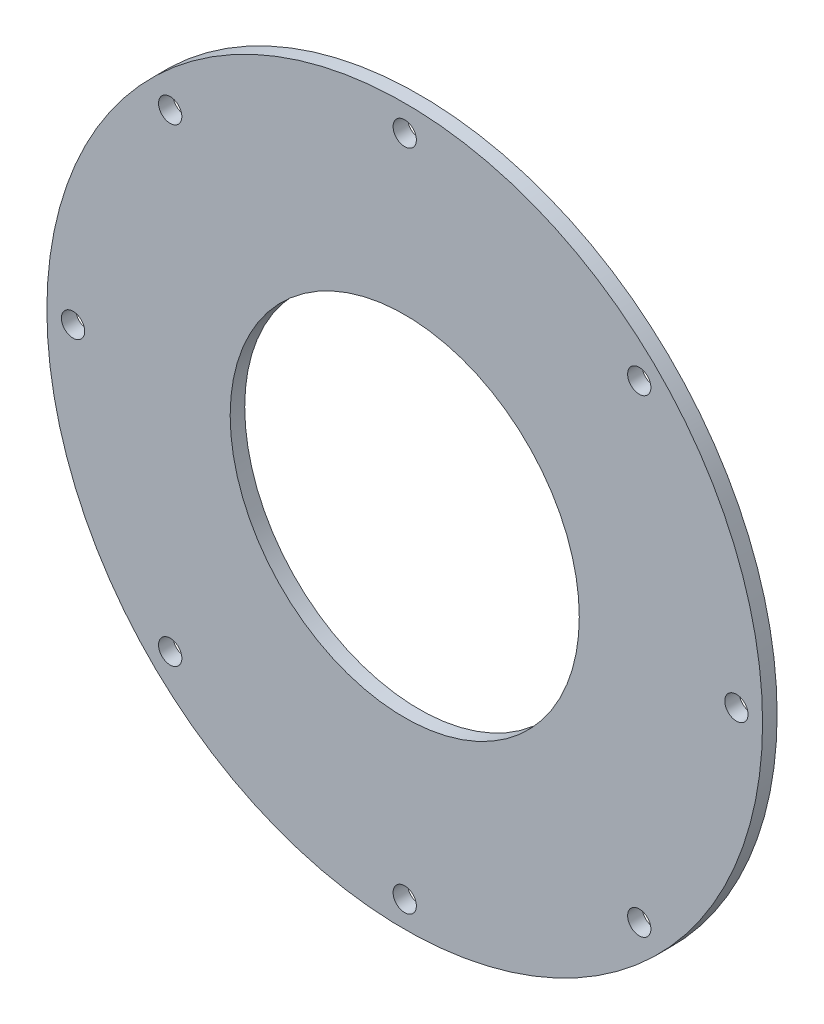
SolidWorks part; units mm, degrees
ref_plane "前视基准面" through (0, 0, 0) normal (0, 0, 1) x (1, 0, 0)
ref_plane "上视基准面" through (0, 0, 0) normal (0, 1, 0) x (1, 0, 0)
ref_plane "右视基准面" through (0, 0, 0) normal (1, 0, 0) x (0, 0, -1)
sketch "草图1" plane through (0, 0, 0) normal (0, 0, 1) x (1, 0, 0)
  line L0 (0, -52.5) -> (0, -61.5) construction
  line L1 (0, 0) -> (36.1973, 0) construction
  line L2 (0, 0) -> (39.2724, -22.6739) construction
  circle A1 centre (0, 0) radius 61.5
  circle A3 centre (0, 0) radius 52.5 construction
  circle A4 centre (0, -57) radius 2
  circle A5 centre (0, -57) radius 3.8 construction
  circle A6 centre (-40.3051, -40.3051) radius 2
  circle A7 centre (-57, 0) radius 2
  circle A8 centre (-40.3051, 40.3051) radius 2
  circle A9 centre (0, 0) radius 23.75 construction
  circle A10 centre (0, 0) radius 22.5 construction
  circle A11 centre (0, -23.75) radius 2.6
  circle A12 centre (-20.5681, 11.875) radius 2.6
  circle A13 centre (20.5681, 11.875) radius 2.6
  circle A14 centre (19.4856, -11.25) radius 2.6
  circle A15 centre (-19.4856, -11.25) radius 2.6
  circle A16 centre (0, 22.5) radius 2.6
  circle A17 centre (0, 0) radius 15.5
  circle A18 centre (0, 57) radius 2
  circle A19 centre (40.3051, 40.3051) radius 2
  circle A20 centre (57, 0) radius 2
  circle A21 centre (40.3051, -40.3051) radius 2
  dimension "D1" = 47.5
  dimension "D2" = 123
  dimension "D3" = 105
  dimension "D4" = 7.6
  dimension "D6" = 45
  dimension "D7" = 5.2
  dimension "D9" = 5.2
  dimension "D10" = 31
  dimension "D8" = 30
  dimension "D5" = 8
extrude "凸台-拉伸1" add sketch "草图1" along normal blind 2.5
sketch "草图2" plane through (0, 0, 2.5) normal (0, 0, 1) x (1, 0, 0)
  circle A0 centre (0, 0) radius 30
  dimension "D1" = 60
extrude "切除-拉伸1" cut sketch "草图2" against normal blind 10
